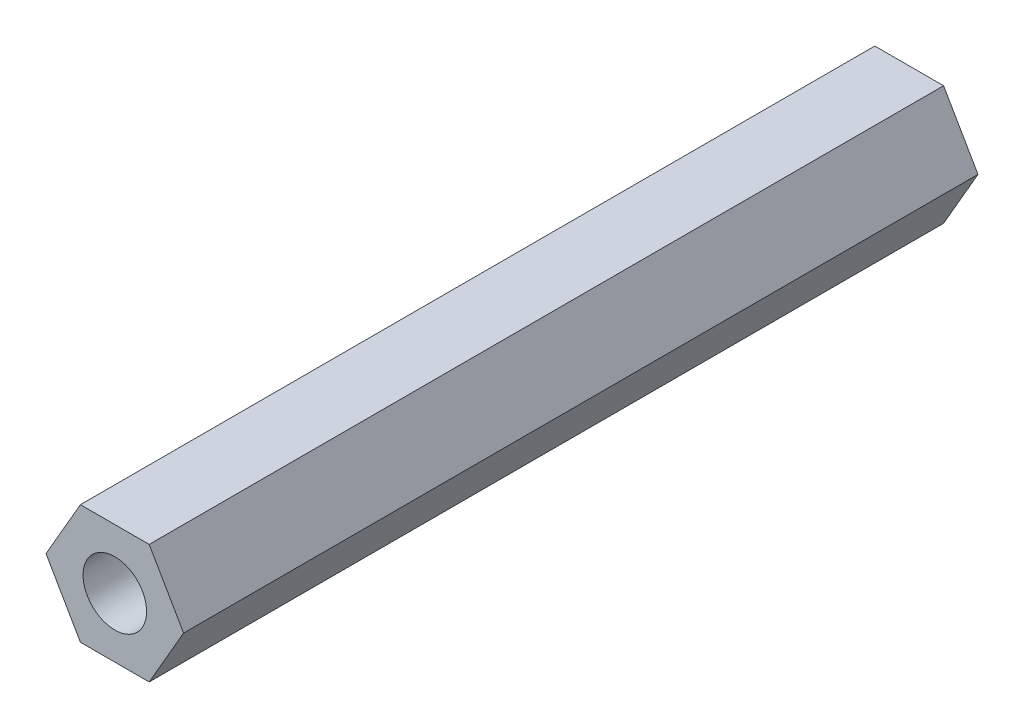
SolidWorks part; units mm, degrees
material "6063-T6"
ref_plane "Front" through (0, 0, 0) normal (0, 0, 1) x (1, 0, 0)
ref_plane "Top" through (0, 0, 0) normal (0, 1, 0) x (1, 0, 0)
ref_plane "Right" through (0, 0, 0) normal (1, 0, 0) x (0, 0, -1)
sketch "Sketch1" plane through (0, 0, 0) normal (0, 0, 1) x (1, 0, 0)
  line L1 (1.7321, -3) -> (3.4641, 0)
  line L2 (3.4641, 0) -> (1.7321, 3)
  line L3 (1.7321, 3) -> (-1.7321, 3)
  line L4 (-1.7321, 3) -> (-3.4641, 0)
  line L5 (-3.4641, 0) -> (-1.7321, -3)
  line L6 (-1.7321, -3) -> (1.7321, -3)
  circle A0 centre (0, 0) radius 3 construction
  circle A1 centre (0, 0) radius 1.6
  dimension "D2" = 3.2
  dimension "D1" = 6
extrude "Boss-Extrude1" add sketch "Sketch1" along normal blind 40
